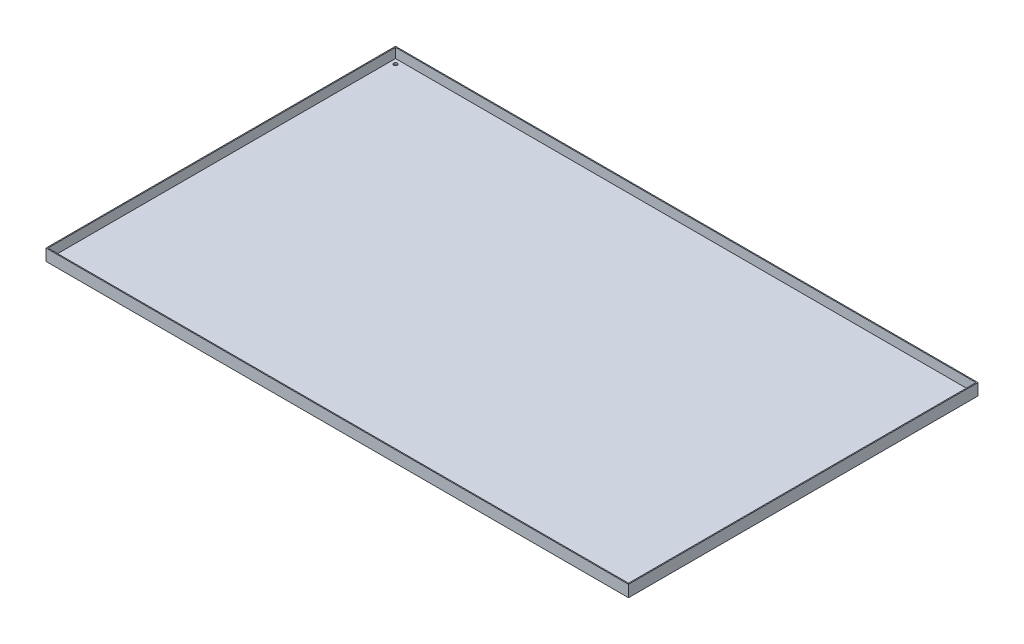
SolidWorks part; units mm, degrees
ref_plane "Front Plane" through (0, 0, 0) normal (0, 0, 1) x (1, 0, 0)
ref_plane "Top Plane" through (0, 0, 0) normal (0, 1, 0) x (1, 0, 0)
ref_plane "Right Plane" through (0, 0, 0) normal (1, 0, 0) x (0, 0, -1)
sketch "Sketch1" plane through (0, 0, 0) normal (0, 1, 0) x (1, 0, 0)
  line L1 (0, 0) -> (3000, 0)
  line L2 (0, 0) -> (0, 1800)
  line L3 (0, 1800) -> (3000, 1800)
  line L4 (3000, 0) -> (3000, 1800)
  dimension "D1" = 1800
  dimension "D2" = 3000
extrude "Boss-Extrude2" add sketch "Sketch1" along normal blind 60
sketch "Sketch2" plane through (0, 60, 0) normal (0, 1, 0) x (1, 0, 0)
  line L0 (3000, 1800) -> (0, 1800) construction
  line L1 (5, 1795) -> (2995, 1795)
  line L2 (5, 1795) -> (5, 5)
  line L3 (5, 5) -> (2995, 5)
  line L4 (2995, 1795) -> (2995, 5)
  line L5 (0, 1800) -> (0, 0) construction
  line L6 (0, 0) -> (3000, 0) construction
  line L7 (3000, 0) -> (3000, 1800) construction
  dimension "D1" = 5
  dimension "D2" = 5
  dimension "D3" = 5
  dimension "D4" = 5
extrude "Cut-Extrude1" cut sketch "Sketch2" against normal blind 50
sketch "Sketch3" plane through (0, 10, 0) normal (0, 1, 0) x (1, 0, 0)
  line L0 (2995, 1795) -> (5, 1795) construction
  line L1 (5, 1795) -> (5, 5) construction
  line L2 (1500, 1864.4614) -> (1500, -113.4472) construction
  line L3 (0, 1800) -> (0, 0) construction
  line L4 (-781.6231, 900) -> (2871.0751, 900) construction
  line L6 (0, 0) -> (3000, 0) construction
  circle A0 centre (30, 1770) radius 10
  circle A1 centre (2970, 1770) radius 10
  circle A2 centre (30, 30) radius 10
  circle A3 centre (2970, 30) radius 10
  dimension "D1" = 20
  dimension "D2" = 25
  dimension "D3" = 25
  dimension "D4" = 1500
  dimension "D5" = 900
extrude "Cut-Extrude2" cut sketch "Sketch3" against normal blind 10
